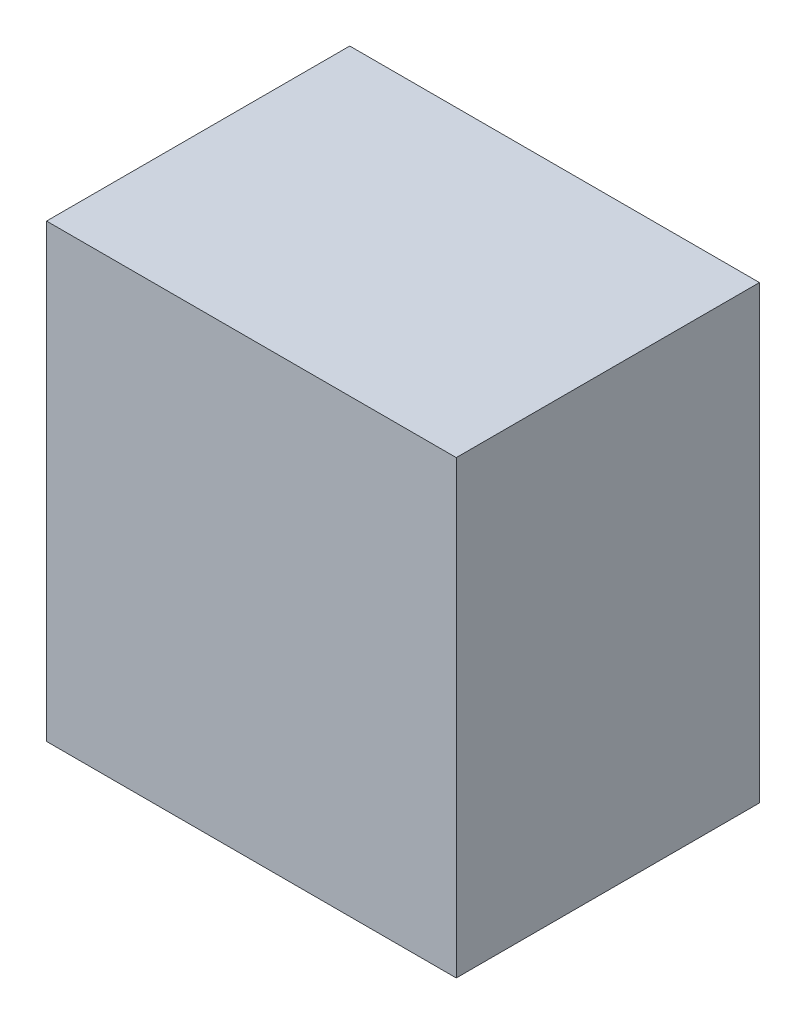
SolidWorks part; units mm, degrees
ref_plane "Plan de face" through (0, 0, 0) normal (0, 0, 1) x (1, 0, 0)
ref_plane "Plan de dessus" through (0, 0, 0) normal (0, 1, 0) x (1, 0, 0)
ref_plane "Plan de droite" through (0, 0, 0) normal (1, 0, 0) x (0, 0, -1)
sketch "Esquisse1" plane through (0, 0, 0) normal (0, 0, 1) x (1, 0, 0)
  line L1 (-25, 27.5) -> (25, 27.5)
  line L2 (-25, 27.5) -> (-25, -27.5)
  line L3 (-25, -27.5) -> (25, -27.5)
  line L4 (25, 27.5) -> (25, -27.5)
  line L5 (-25, 27.5) -> (25, -27.5) construction
  line L6 (-25, -27.5) -> (25, 27.5) construction
  point P0 (0, 0)
  point P5 (0, 0)
  dimension "D1" = 55
  dimension "D2" = 50
extrude "Boss.-Extru.1" add sketch "Esquisse1" along normal blind 37
sketch "Esquisse2" plane through (0, 0, 0) normal (0, 0, 1) x (1, 0, 0)
  circle A0 centre (0, 0) radius 7.5
  dimension "D1" = 15
extrude "Boss.-Extru.2" add sketch "Esquisse2" against normal blind 10
fillet "Congé3" radius 2 1 edges at (7.5, 0, -10)
